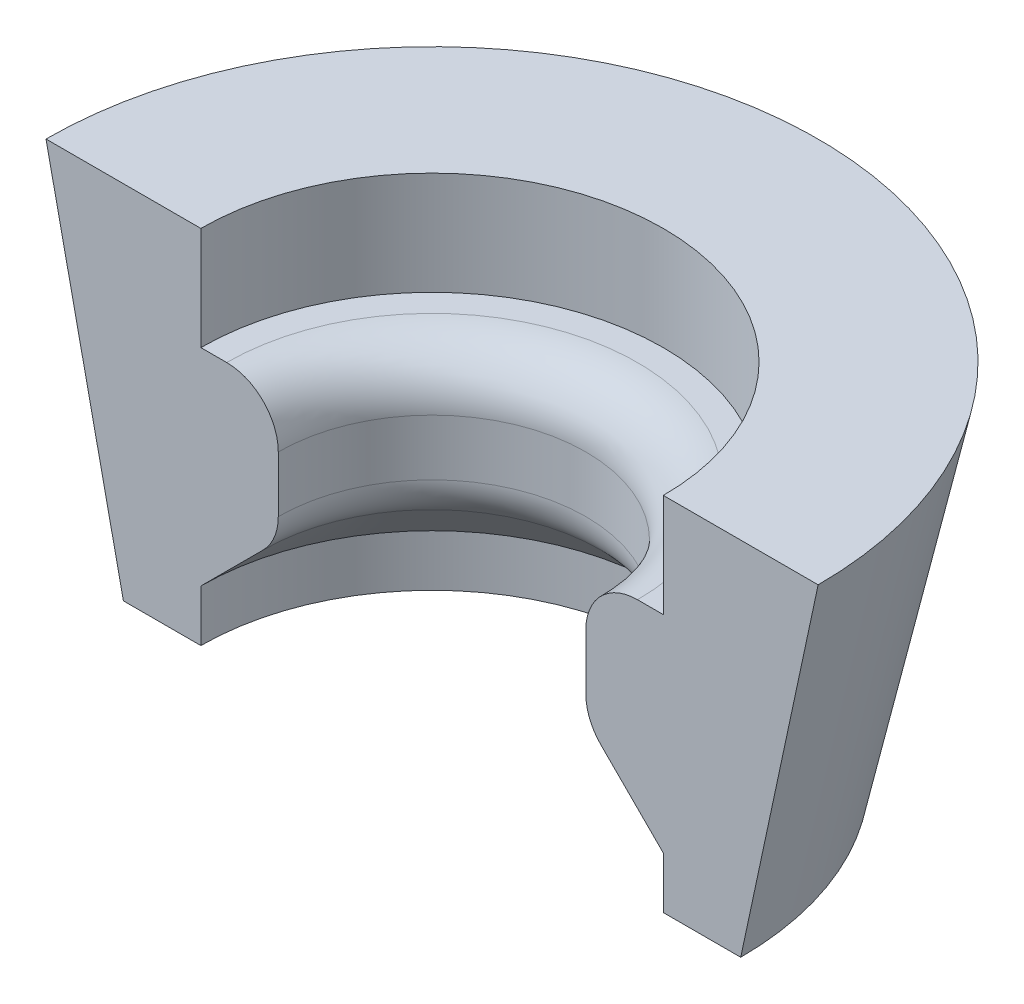
SolidWorks part; units mm, degrees
ref_plane "Front Plane" through (0, 0, 0) normal (0, 0, 1) x (1, 0, 0)
ref_plane "Top Plane" through (0, 0, 0) normal (0, 1, 0) x (1, 0, 0)
ref_plane "Right Plane" through (0, 0, 0) normal (1, 0, 0) x (0, 0, -1)
sketch "Sketch1" plane through (0, 0, 0) normal (0, 0, 1) x (1, 0, 0)
  line L0 (-3.556, 1.5875) -> (-3.556, 3.175)
  line L1 (-3.556, 1.5875) -> (3.556, 1.5875) construction
  line L2 (-3.556, 1.5875) -> (-3.556, -1.5875) construction
  line L3 (-3.556, -1.5875) -> (3.556, -1.5875) construction
  line L4 (3.556, 1.5875) -> (3.556, -1.5875) construction
  line L5 (-3.556, 1.5875) -> (3.556, -1.5875) construction
  line L6 (-3.556, -1.5875) -> (3.556, 1.5875) construction
  line L7 (-3.556, 3.175) -> (-5.9372, 3.175)
  line L8 (-5.9372, 3.175) -> (-4.7466, -2.3812)
  line L9 (-4.7466, -2.3812) -> (-3.556, -2.3812)
  line L10 (-3.556, -2.3812) -> (-3.556, -1.5875)
  line L11 (-3.556, 1.5875) -> (-3.1591, 1.5875)
  line L12 (-2.3654, 0.7937) -> (-2.3654, -0.0681)
  line L13 (-2.5979, -0.6294) -> (-3.556, -1.5875)
  line L14 (0, 1.5875) -> (0, -1.5875) construction
  arc A0 (-3.1591, 1.5875) -> (-2.3654, 0.7937) centre (-3.1591, 0.7938) cw
  arc A1 (-2.3654, -0.0681) -> (-2.5979, -0.6294) centre (-3.1591, -0.0681) cw
  point P0 (0, 0)
  point P14 (-2.3654, 1.5875)
  dimension "D9" = 0.7937
  dimension "D1" = 7.112
  dimension "D2" = 3.175
  dimension "D3" = 2.3812
  dimension "D4" = 1.1906
  dimension "D5" = 0.7937
  dimension "D6" = 1.5875
  dimension "D7" = 45
  dimension "D8" = 1.1906
revolve "Revolve1" add sketch "Sketch1" angle 180 about L14
